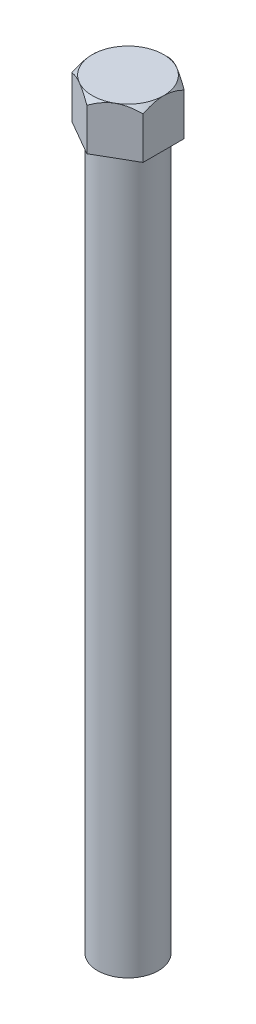
SolidWorks part; units mm, degrees
ref_plane "Front Plane" through (0, 0, 0) normal (0, 0, 1) x (1, 0, 0)
ref_plane "Top Plane" through (0, 0, 0) normal (0, 1, 0) x (1, 0, 0)
ref_plane "Right Plane" through (0, 0, 0) normal (1, 0, 0) x (0, 0, -1)
sketch "Sketch1" plane through (0, 0, 0) normal (0, 1, 0) x (1, 0, 0)
  line L0 (-0.4768, 0) -> (0.4172, 0) construction
  line L1 (0, 0.2271) -> (0, -0.2313) construction
  line L3 (0.15, 0.0866) -> (0, 0.1732)
  line L4 (0, 0.1732) -> (-0.15, 0.0866)
  line L5 (-0.15, 0.0866) -> (-0.15, -0.0866)
  line L6 (-0.15, -0.0866) -> (0, -0.1732)
  line L7 (0, -0.1732) -> (0.15, -0.0866)
  line L8 (0.15, -0.0866) -> (0.15, 0.0866)
  circle A1 centre (0, 0) radius 0.15 construction
  dimension "D2" = 0.3
extrude "Boss-Extrude1" add sketch "Sketch1" along normal blind 0.2
sketch "Sketch2" plane through (0, 0, 0) normal (0, -1, 0) x (1, 0, 0)
  circle A0 centre (0, 0) radius 0.1282
  dimension "D1" = 0.2565
extrude "Boss-Extrude2" add sketch "Sketch2" along normal blind 3
sketch "Sketch7" plane through (0, 0.2, 0) normal (0, 1, 0) x (1, 0, 0)
  circle A0 centre (0, 0) radius 0.15
extrude "Cut-Extrude2" cut sketch "Sketch7" against normal blind 0.03 draft 45 flip side to cut
